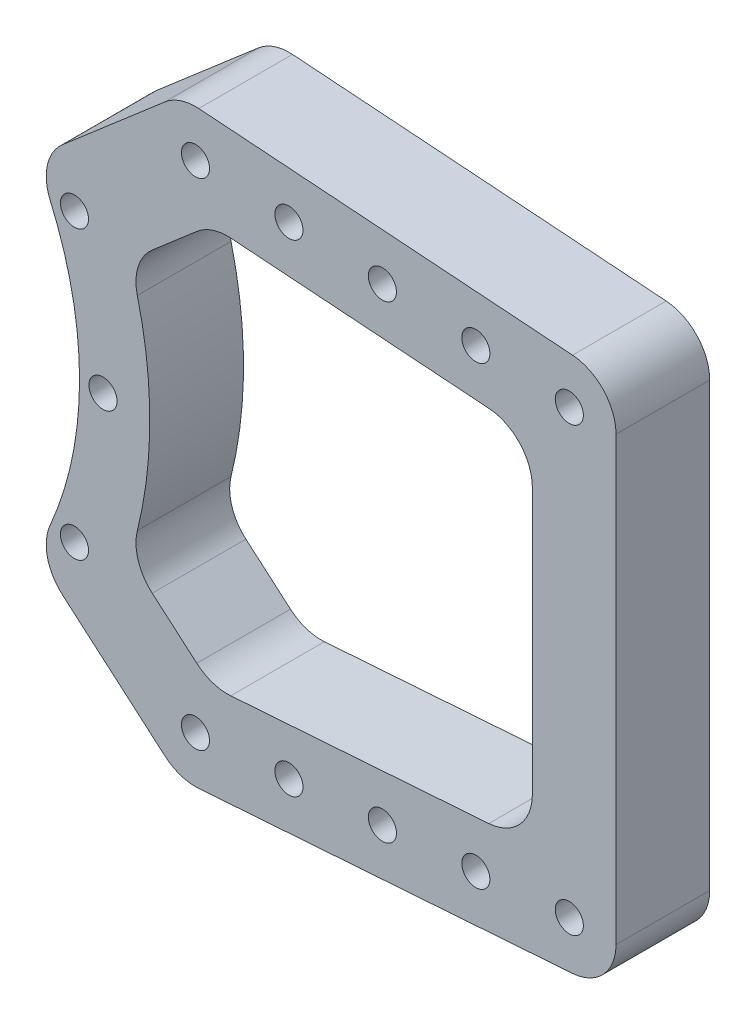
SolidWorks part; units mm, degrees
ref_plane "前视基准面" through (0, 0, 0) normal (0, 0, 1) x (1, 0, 0)
ref_plane "上视基准面" through (0, 0, 0) normal (0, 1, 0) x (1, 0, 0)
ref_plane "右视基准面" through (0, 0, 0) normal (1, 0, 0) x (0, 0, -1)
other "Configuration Table"
sketch "草图3" plane through (0, 0, 0) normal (0, 0, 1) x (1, 0, 0)
  line L0 (36.9552, -15.3073) -> (49.8729, -26.4376)
  line L1 (49.8729, -26.4376) -> (99.7459, -22.8753)
  line L2 (99.7459, -22.8753) -> (109.9739, -12.4372)
  line L3 (36.9552, 15.3073) -> (49.8729, 26.4376)
  line L4 (49.8729, 26.4376) -> (99.7459, 22.8753)
  line L5 (99.7459, 22.8753) -> (109.9739, 12.4372)
  line L6 (32.4388, -18.0159) -> (48.1718, -31.5719)
  line L7 (48.1718, -31.5719) -> (101.9915, -27.7276)
  line L8 (101.9915, -27.7276) -> (114.1851, -15.2836)
  line L9 (40.2189, -11.5195) -> (51.5741, -21.3034)
  line L10 (51.5741, -21.3034) -> (97.5003, -18.023)
  line L11 (97.5003, -18.023) -> (106.4026, -8.9378)
  line L12 (40.2189, 11.5195) -> (51.5741, 21.3034)
  line L13 (51.5741, 21.3034) -> (97.5003, 18.023)
  line L14 (97.5003, 18.023) -> (106.4026, 8.9378)
  line L15 (32.0167, 17.6522) -> (48.1718, 31.5719)
  line L16 (48.1718, 31.5719) -> (101.9915, 27.7276)
  line L17 (101.9915, 27.7276) -> (114.1732, 15.2957)
  line L18 (33.6914, -19.0952) -> (48.1718, -31.5719) construction
  line L19 (33.6914, 19.0952) -> (48.1718, 31.5719) construction
  line L20 (101.9915, -27.7276) -> (113.5452, -15.9366) construction
  line L21 (101.9915, 27.7276) -> (113.5452, 15.9366) construction
  line L22 (112.379, 17.1268) -> (115.1724, 14.276)
  circle A0 centre (140, 0) radius 32.5
  circle A1 centre (0, 0) radius 40
  circle A2 centre (140, 0) radius 35
  circle A4 centre (0, 0) radius 45
  circle A5 centre (0, 0) radius 37.5
  circle A6 centre (140, 0) radius 30
  dimension "D5" = 75
  dimension "D6" = 60
  dimension "D1" = 5
  dimension "D2" = 5
  dimension "D3" = 5
  dimension "D4" = 5
extrude "凸台-拉伸1" add sketch "草图3" along normal blind 15
fillet "圆角1" radius 5 1 edges at (101.9915, 27.7276, 7.5)
fillet "圆角2" radius 5 1 edges at (114.1851, 15.2836, 7.5)
fillet "圆角3" radius 5 1 edges at (114.1851, -15.2836, 7.5)
fillet "圆角4" radius 5 1 edges at (101.9915, -27.7276, 7.5)
fillet "圆角5" radius 5 1 edges at (48.1718, -31.5719, 7.5)
fillet "圆角6" radius 5 1 edges at (48.1718, 31.5719, 7.5)
fillet "圆角7" radius 5 1 edges at (32.7436, -18.2785, 7.5)
fillet "圆角8" radius 5 1 edges at (32.7436, 18.2785, 7.5)
fillet "圆角9" radius 5 1 edges at (97.5003, -18.023, 7.5)
fillet "圆角10" radius 5 1 edges at (106.2123, -9.132, 7.5)
fillet "圆角11" radius 5 1 edges at (106.2123, 9.132, 7.5)
fillet "圆角12" radius 5 1 edges at (97.5003, 18.023, 7.5)
fillet "圆角13" radius 5 1 edges at (51.5741, -21.3034, 7.5)
fillet "圆角14" radius 5 1 edges at (42.8391, -13.7771, 7.5)
fillet "圆角15" radius 5 1 edges at (42.8391, 13.7771, 7.5)
fillet "圆角16" radius 5 1 edges at (51.5741, 21.3034, 7.5)
sketch "草图5" plane through (0, 0, 0) normal (0, 0, -1) x (-1, 0, 0)
  circle A0 centre (-36.9552, 15.3073) radius 1.5
  circle A1 centre (-40, 0) radius 1.5
  circle A2 centre (-36.9552, -15.3073) radius 1.5
  circle A3 centre (-49.8729, -26.4376) radius 1.5
  circle A4 centre (-49.8729, 26.4376) radius 1.5
  circle A5 centre (-99.7459, 22.8753) radius 1.5
  circle A6 centre (-99.7459, -22.8753) radius 1.5
  circle A7 centre (-109.9739, 12.4372) radius 1.5
  circle A8 centre (-107.5, 0) radius 1.5
  circle A9 centre (-109.9739, -12.4372) radius 1.5
  circle A10 centre (-59.8475, 25.7252) radius 1.5
  circle A11 centre (-69.8221, 25.0127) radius 1.5
  circle A12 centre (-79.7967, 24.3002) radius 1.5
  circle A13 centre (-89.7713, 23.5878) radius 1.5
  circle A14 centre (-89.7713, -23.5878) radius 1.5
  circle A15 centre (-79.7967, -24.3002) radius 1.5
  circle A16 centre (-69.8221, -25.0127) radius 1.5
  circle A17 centre (-59.8475, -25.7252) radius 1.5
extrude "切除-拉伸1" cut sketch "草图5" against normal blind 15
sketch "草图6" plane through (0, 0, 15) normal (0, 0, 1) x (1, 0, 0)
  line L0 (100.1021, 27.8626) -> (100.1021, -27.8626)
  line L1 (100.1021, 27.8626) -> (115.1226, 26.777)
  line L2 (4.9746, 34.6447) -> (140, 25) construction
  line L3 (115.1226, 26.777) -> (132.6157, -67.8734)
  line L4 (132.6157, -67.8734) -> (100.1021, -27.8626)
  line L5 (99.7459, 22.8753) -> (89.7713, 23.5878)
  line L6 (99.7459, -22.8753) -> (89.7713, -23.5878)
  line L7 (94.7586, 23.2315) -> (94.7586, -23.2315)
  line L8 (94.7586, 23.2315) -> (94.7586, 28.2443)
  line L9 (50.2292, 31.4249) -> (100.1021, 27.8626) construction
  line L10 (94.7586, 28.2443) -> (100.1021, 27.8626)
  line L11 (94.7586, -23.2315) -> (94.7586, -28.2443)
  line L12 (50.2292, -31.4249) -> (100.1021, -27.8626) construction
  line L13 (94.7586, -28.2443) -> (100.1021, -27.8626)
  circle M8 centre (109.9739, -12.4372) radius 1.5
  circle M13 centre (107.5, 0) radius 1.5
  circle M14 centre (109.9739, 12.4372) radius 1.5
  circle M15 centre (99.7459, -22.8753) radius 1.5
  circle M16 centre (99.7459, 22.8753) radius 1.5
  line M24 (53.6315, 21.1564) -> (95.6109, 18.1579)
  arc M25 (95.6109, 18.1579) -> (98.826, 16.67) centre (95.2547, 13.1706) cw
  line M26 (98.826, 16.67) -> (104.2974, 11.0863)
  arc M27 (104.2974, 11.0863) -> (105.6353, 6.6385) centre (100.7261, 7.5869) cw
  arc M28 (105.6353, 6.6385) -> (105.6353, -6.6385) centre (140, 0) ccw
  arc M29 (105.6353, -6.6385) -> (104.2974, -11.0863) centre (100.7261, -7.5869) cw
  line M30 (104.2974, -11.0863) -> (98.826, -16.67)
  arc M31 (98.826, -16.67) -> (95.6109, -18.1579) centre (95.2547, -13.1706) cw
  line M32 (95.6109, -18.1579) -> (53.6315, -21.1564)
  line M45 (50.2292, -31.4249) -> (100.1021, -27.8626)
  arc M46 (100.1021, -27.8626) -> (103.3172, -26.3747) centre (99.7459, -22.8753) ccw
  line M47 (103.3172, -26.3747) -> (111.6554, -17.8652)
  arc M48 (111.6554, -17.8652) -> (112.6435, -12.3136) centre (108.0841, -14.3658) ccw
  arc M49 (112.6435, -12.3136) -> (112.6435, 12.3136) centre (140, 0) cw
  arc M50 (112.6435, 12.3136) -> (111.6554, 17.8652) centre (108.0841, 14.3658) ccw
  line M51 (111.6554, 17.8652) -> (103.3172, 26.3747)
  arc M52 (103.3172, 26.3747) -> (100.1021, 27.8626) centre (99.7459, 22.8753) ccw
  line M53 (100.1021, 27.8626) -> (50.2292, 31.4249)
extrude "切除-拉伸5" cut sketch "草图6" against normal blind 15 contours L0 M52 M16 M26 M27 M28 M29 M30 M15 M46 M47 M48 M49 M50 M51 M13 M14 M8 | L7 L6 L0 M32 M15 M30 M31 | L6 L11 L0 M45 M15 | L5 L7 L0 M24 M25 M26 M16 | L8 L5 L0 M16 M53
sketch "草图7" plane through (0, 0, 15) normal (0, 0, 1) x (1, 0, 0)
  line L0 (94.7586, 18.2188) -> (85.8268, 18.8568)
  line L1 (94.7586, 28.2443) -> (85.8268, 28.2443)
  line L2 (94.7586, 28.2443) -> (94.7586, -28.2443)
  line L3 (94.7586, -28.2443) -> (85.8268, -28.2443)
  line L4 (85.8268, 28.2443) -> (85.8268, -28.2443)
  line L5 (53.6315, 21.1564) -> (94.7586, 18.2188) construction
  line L6 (94.7586, -18.2188) -> (85.8268, -18.8568)
  line L7 (53.6315, -21.1564) -> (94.7586, -18.2188) construction
  line M3 (94.7586, -18.2188) -> (53.6315, -21.1564)
  line M11 (53.6315, 21.1564) -> (94.7586, 18.2188)
extrude "凸台-拉伸2" add sketch "草图7" against normal blind 15 contours L4 L2 M11 M3
fillet "圆角17" radius 5 1 edges at (94.7586, 28.2443, 7.5)
fillet "圆角18" radius 5 1 edges at (94.7586, -28.2443, 7.5)
fillet "圆角19" radius 5 1 edges at (85.8268, 18.8568, 7.5)
fillet "圆角20" radius 5 1 edges at (85.8268, -18.8568, 7.5)
sketch "草图8" plane through (0, 0, 0) normal (0, 0, -1) x (-1, 0, 0)
  line L1 (-115.5106, 32.3706) -> (-18.9905, 32.3706)
  line L2 (-115.5106, 32.3706) -> (-115.5106, -39.9455)
  line L3 (-115.5106, -39.9455) -> (-18.9905, -39.9455)
  line L4 (-18.9905, 32.3706) -> (-18.9905, -39.9455)
  line L5 (-115.5106, 32.3706) -> (-18.9905, -39.9455) construction
  line L6 (-115.5106, -39.9455) -> (-18.9905, 32.3706) construction
  point P0 (-67.2506, -3.7874)
  point P5 (-18.9905, -39.9455)
extrude "切除-拉伸6" cut sketch "草图8" against normal blind 5
